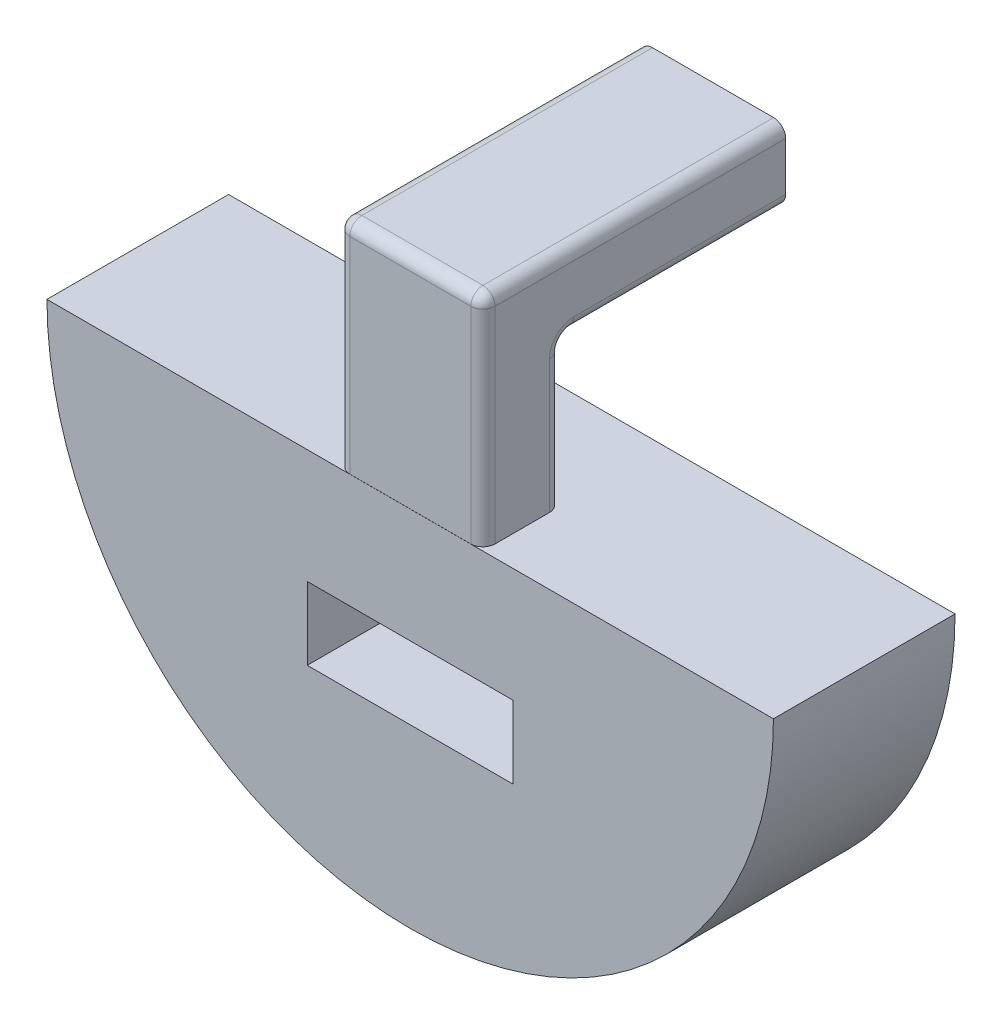
SolidWorks part; units mm, degrees
ref_plane "Спереди" through (0, 0, 0) normal (0, 0, 1) x (1, 0, 0)
ref_plane "Сверху" through (0, 0, 0) normal (0, 1, 0) x (1, 0, 0)
ref_plane "Справа" through (0, 0, 0) normal (1, 0, 0) x (0, 0, -1)
sketch "Эскиз1" plane through (0, 0, 0) normal (0, 0, 1) x (1, 0, 0)
  line L0 (30, 0) -> (-30, 0)
  line L1 (0, 0) -> (0, -33.2147) construction
  line L3 (-8.5, -9.4266) -> (8.5, -9.4266)
  line L4 (-8.5, -9.4266) -> (-8.5, -15.4266)
  line L5 (-8.5, -15.4266) -> (8.5, -15.4266)
  line L6 (8.5, -9.4266) -> (8.5, -15.4266)
  line L7 (-8.5, -9.4266) -> (8.5, -15.4266) construction
  line L8 (-8.5, -15.4266) -> (8.5, -9.4266) construction
  arc A0 (-30, 0) -> (30, 0) centre (0, 0) ccw
  point P1 (0, -12.4266)
  dimension "D1" = 17
  dimension "D3" = 30
  dimension "D2" = 6
extrude "Бобышка-Вытянуть1" add sketch "Эскиз1" along normal blind 15
sketch "Эскиз6" plane through (0, 0, 0) normal (1, 0, 0) x (0, 0, -1)
  line L0 (-14.9904, -0.0021) -> (-14.9904, 17.9979)
  line L1 (-14.9904, 17.9979) -> (10.0096, 17.9979)
  line L2 (10.0096, 17.9979) -> (10.0096, 11.9979)
  line L3 (10.0096, 11.9979) -> (-8.4982, 11.9979)
  line L4 (-8.4982, 11.9979) -> (-8.4982, -0.0021)
  line L5 (-8.4982, -0.0021) -> (-14.9904, -0.0021)
  dimension "D1" = 12
  dimension "D2" = 6
  dimension "D3" = 25
  dimension "D4" = 18
extrude "Бобышка-Вытянуть2" add sketch "Эскиз6" along normal blind 6 and the other way blind 6
fillet "Скругление4" radius 1 1 edges at (-6, 8.9989, 14.9904)
fillet "Скругление5" radius 1 5 edges at (0.5, 17.9979, 14.9904) (-5.7071, 17.9979, 14.6975) (-6, 17.9979, 1.9904) (6, 17.9979, 2.4904) (6, 8.9989, 14.9904)
fillet "Скругление6" radius 1 5 edges at (6, 11.9979, -0.7557) (-6, 11.9979, -0.7557) (6, 5.9989, 8.4982) (-6, 5.9989, 8.4982) (0, 11.9979, 8.4982)
